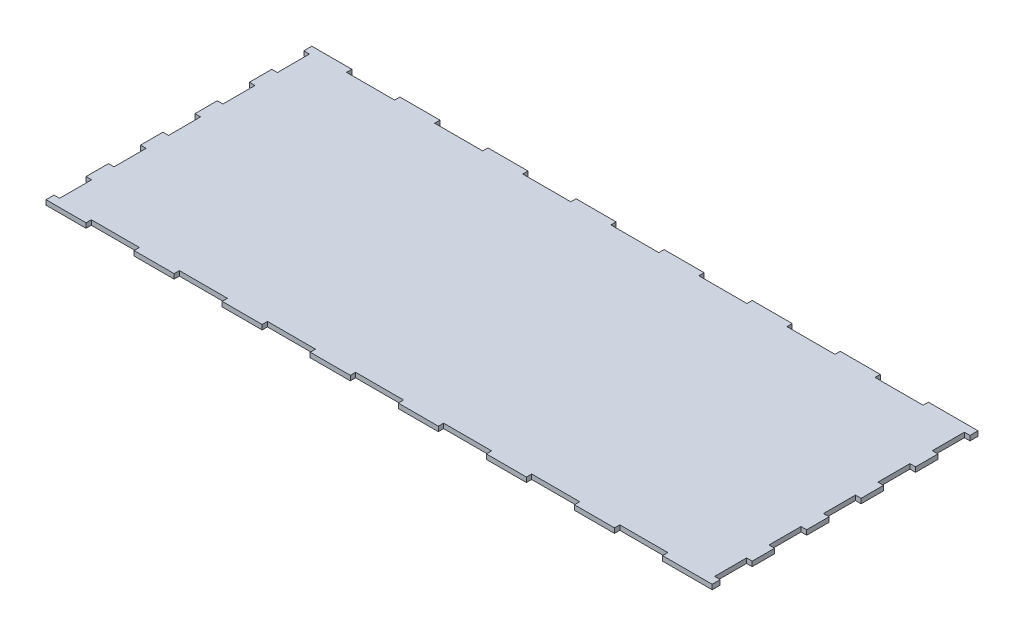
SolidWorks part; units mm, degrees
material "Teak"
ref_plane "Front Plane" through (0, 0, 0) normal (0, 0, 1) x (1, 0, 0)
ref_plane "Top Plane" through (0, 0, 0) normal (0, 1, 0) x (1, 0, 0)
ref_plane "Right Plane" through (0, 0, 0) normal (1, 0, 0) x (0, 0, -1)
sketch "Sketch1" plane through (0, 0, 0) normal (0, 1, 0) x (1, 0, 0)
  line L0 (-208, 83) -> (208, 83)
  line L5 (-200, 75) -> (200, 75) construction
  line L6 (-200, 75) -> (-200, -75) construction
  line L7 (-200, -75) -> (200, -75) construction
  line L8 (200, 75) -> (200, -75) construction
  line L9 (208, 83) -> (208, -83)
  line L10 (-208, -83) -> (208, -83)
  line L11 (-208, 83) -> (-208, -83)
  point P8 (0, 75)
  point P10 (-200, 0)
  dimension "D1" = 150
  dimension "D2" = 400
  dimension "D3" = 8
extrude "Boss-Extrude1" add sketch "Sketch1" along normal blind 3
sketch "Sketch2" plane through (0, 3, 0) normal (0, 1, 0) x (1, 0, 0)
  line L0 (208, 83) -> (-208, 83) construction
  line L1 (-183, 83) -> (-153, 83)
  line L2 (-183, 83) -> (-183, 79.7)
  line L3 (-183, 79.7) -> (-153, 79.7)
  line L4 (-153, 83) -> (-153, 79.7)
  line L5 (-208, 83) -> (-208, -83) construction
  line L6 (-128, 83) -> (-128, 79.7)
  line L7 (-128, 83) -> (-98, 83)
  line L8 (-98, 83) -> (-98, 79.7)
  line L9 (-128, 79.7) -> (-98, 79.7)
  line L10 (-73, 83) -> (-73, 79.7)
  line L11 (-73, 83) -> (-43, 83)
  line L12 (-43, 83) -> (-43, 79.7)
  line L13 (-73, 79.7) -> (-43, 79.7)
  line L14 (-18, 83) -> (-18, 79.7)
  line L15 (-18, 83) -> (12, 83)
  line L16 (12, 83) -> (12, 79.7)
  line L17 (-18, 79.7) -> (12, 79.7)
  line L18 (37, 83) -> (37, 79.7)
  line L19 (37, 83) -> (67, 83)
  line L20 (67, 83) -> (67, 79.7)
  line L21 (37, 79.7) -> (67, 79.7)
  line L22 (92, 83) -> (92, 79.7)
  line L23 (92, 83) -> (122, 83)
  line L24 (122, 83) -> (122, 79.7)
  line L25 (92, 79.7) -> (122, 79.7)
  line L26 (147, 83) -> (147, 79.7)
  line L27 (147, 83) -> (177, 83)
  line L28 (177, 83) -> (177, 79.7)
  line L29 (147, 79.7) -> (177, 79.7)
  line L30 (-208, 0) -> (208, 0) construction
  line L31 (208, -83) -> (208, 83) construction
  line L32 (0, -83) -> (0, 83) construction
  line L33 (-208, -83) -> (208, -83) construction
  line L34 (147, -79.7) -> (177, -79.7)
  line L35 (177, -83) -> (177, -79.7)
  line L36 (147, -83) -> (177, -83)
  line L37 (147, -83) -> (147, -79.7)
  line L38 (92, -79.7) -> (122, -79.7)
  line L39 (122, -83) -> (122, -79.7)
  line L40 (92, -83) -> (122, -83)
  line L41 (92, -83) -> (92, -79.7)
  line L42 (37, -79.7) -> (67, -79.7)
  line L43 (67, -83) -> (67, -79.7)
  line L44 (37, -83) -> (67, -83)
  line L45 (37, -83) -> (37, -79.7)
  line L46 (-18, -79.7) -> (12, -79.7)
  line L47 (12, -83) -> (12, -79.7)
  line L48 (-18, -83) -> (12, -83)
  line L49 (-18, -83) -> (-18, -79.7)
  line L50 (-73, -79.7) -> (-43, -79.7)
  line L51 (-43, -83) -> (-43, -79.7)
  line L52 (-73, -83) -> (-43, -83)
  line L53 (-73, -83) -> (-73, -79.7)
  line L54 (-128, -79.7) -> (-98, -79.7)
  line L55 (-98, -83) -> (-98, -79.7)
  line L56 (-128, -83) -> (-98, -83)
  line L57 (-128, -83) -> (-128, -79.7)
  line L58 (-153, -83) -> (-153, -79.7)
  line L59 (-183, -79.7) -> (-153, -79.7)
  line L60 (-183, -83) -> (-183, -79.7)
  line L61 (-183, -83) -> (-153, -83)
  line L62 (-208, -24) -> (-208, -44)
  line L63 (-208, 10) -> (-204.5, 10)
  line L64 (-208, 10) -> (-208, -10)
  line L65 (-208, -10) -> (-204.5, -10)
  line L66 (-204.5, 10) -> (-204.5, -10)
  line L67 (-208, -24) -> (-204.5, -24)
  line L68 (-204.5, -24) -> (-204.5, -44)
  line L69 (-208, -44) -> (-204.5, -44)
  line L70 (-208, -58) -> (-208, -78)
  line L71 (-208, -58) -> (-204.5, -58)
  line L72 (-204.5, -58) -> (-204.5, -78)
  line L73 (-208, -78) -> (-204.5, -78)
  line L74 (-208, 44) -> (-208, 24)
  line L75 (-208, 44) -> (-204.5, 44)
  line L76 (-204.5, 44) -> (-204.5, 24)
  line L77 (-208, 24) -> (-204.5, 24)
  line L78 (-208, 78) -> (-208, 58)
  line L79 (-208, 78) -> (-204.5, 78)
  line L80 (-204.5, 78) -> (-204.5, 58)
  line L81 (-208, 58) -> (-204.5, 58)
  line L82 (208, -58) -> (204.5, -58)
  line L83 (204.5, -58) -> (204.5, -78)
  line L84 (208, -78) -> (204.5, -78)
  line L85 (208, -58) -> (208, -78)
  line L86 (208, -24) -> (204.5, -24)
  line L87 (204.5, -24) -> (204.5, -44)
  line L88 (208, -44) -> (204.5, -44)
  line L89 (208, -24) -> (208, -44)
  line L90 (208, -10) -> (204.5, -10)
  line L91 (204.5, 10) -> (204.5, -10)
  line L92 (208, 10) -> (204.5, 10)
  line L93 (208, 10) -> (208, -10)
  line L94 (208, 44) -> (204.5, 44)
  line L95 (204.5, 44) -> (204.5, 24)
  line L96 (208, 24) -> (204.5, 24)
  line L97 (208, 44) -> (208, 24)
  line L98 (208, 78) -> (204.5, 78)
  line L99 (204.5, 78) -> (204.5, 58)
  line L100 (208, 58) -> (204.5, 58)
  line L101 (208, 78) -> (208, 58)
  point P73 (-204.5, 0)
  dimension "D1" = 3.3
  dimension "D2" = 25
  dimension "D3" = 30
  dimension "D5" = 25
  dimension "D6" = 3.5
  dimension "D7" = 20
  dimension "D10" = 14
  dimension "D11" = 14
  dimension "D4" = 7
  dimension "D8" = 3
  dimension "D9" = 3
extrude "Cut-Extrude1" cut sketch "Sketch2" against normal blind 3
